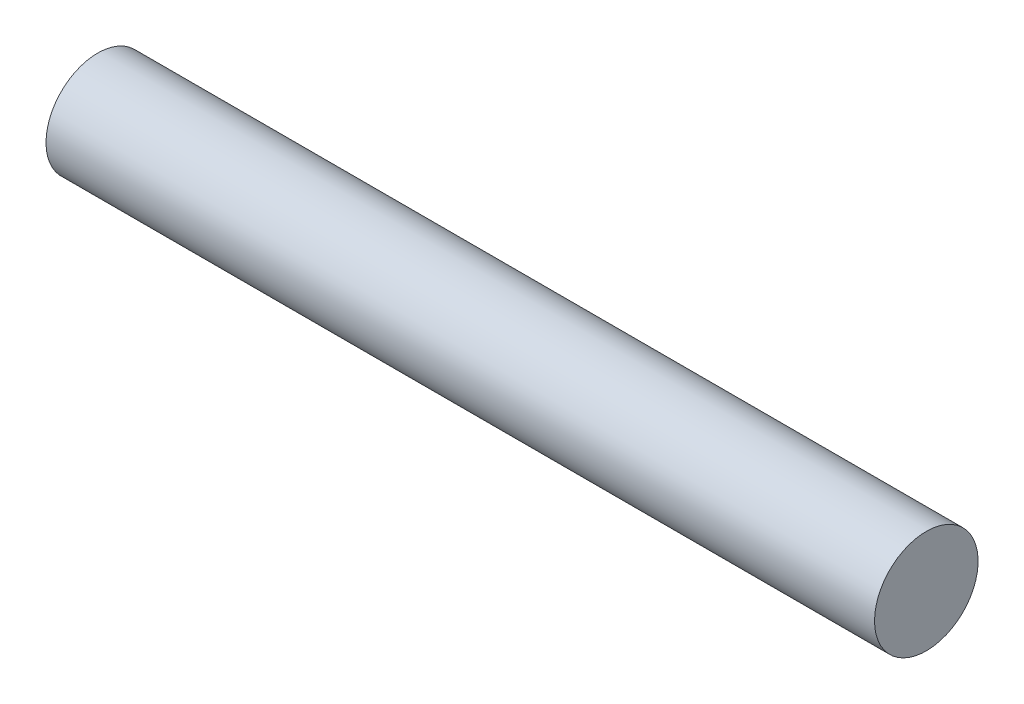
SolidWorks part; units mm, degrees
material "AISI 304"
ref_plane "Front Plane" through (0, 0, 0) normal (0, 0, 1) x (1, 0, 0)
ref_plane "Top Plane" through (0, 0, 0) normal (0, 1, 0) x (1, 0, 0)
ref_plane "Right Plane" through (0, 0, 0) normal (1, 0, 0) x (0, 0, -1)
sketch "Sketch1" plane through (0, 0, 0) normal (1, 0, 0) x (0, 0, -1)
  circle A0 centre (0, 0) radius 2.3812
  dimension "D1" = 4.7625
extrude "Boss-Extrude1" add sketch "Sketch1" along normal mid plane 38.1
